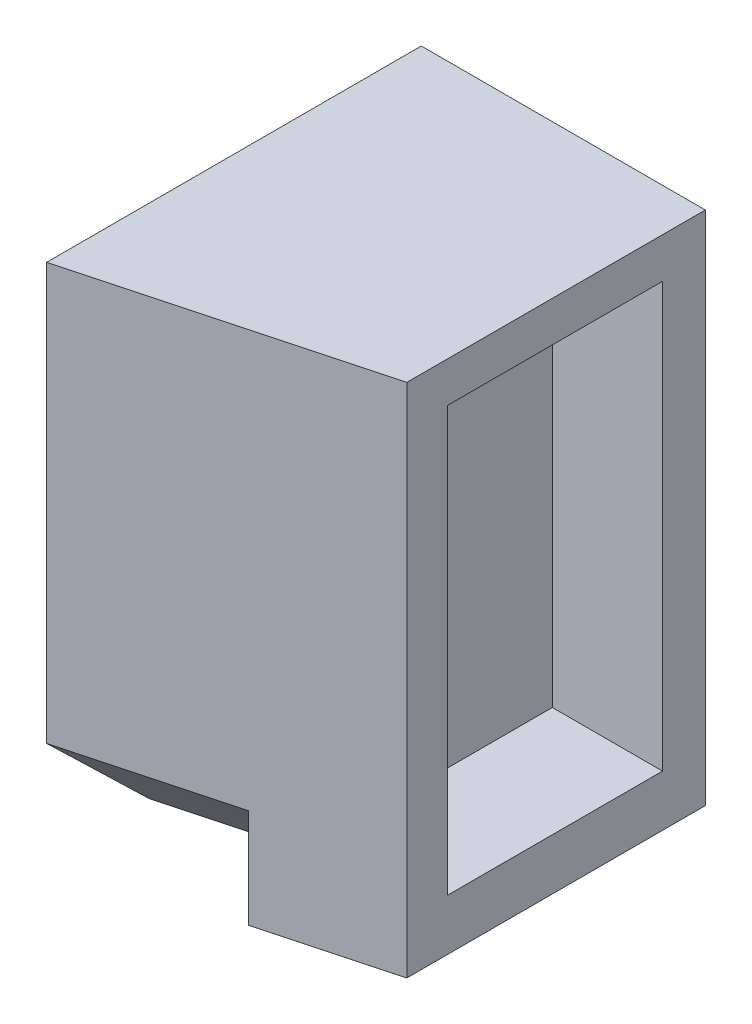
SolidWorks part; units mm, degrees
ref_plane "Front Plane" through (0, 0, 0) normal (0, 0, 1) x (1, 0, 0)
ref_plane "Top Plane" through (0, 0, 0) normal (0, 1, 0) x (1, 0, 0)
ref_plane "Right Plane" through (0, 0, 0) normal (1, 0, 0) x (0, 0, -1)
sketch3d "3DSketch1"
  line L2 (0, 594.6103, 215.9) -> (0, 0, 215.9) construction
  line L3 (327.3856, 0, 431.8) -> (327.3856, 0, 0) construction
  line L6 (0, 0, 0) -> (0, 594.6103, 0) construction
  line L7 (327.3856, 594.6103, 431.8) -> (327.3856, 594.6103, 0) construction
  line L8 (327.3856, 594.6103, 0) -> (327.3856, 0, 0) construction
  line L9 (0, 0, 431.8) -> (0, 594.6103, 431.8) construction
  line L10 (327.3856, 594.6103, 431.8) -> (0, 594.6103, 431.8) construction
  line L11 (327.3856, 0, 431.8) -> (327.3856, 594.6103, 431.8) construction
  line L12 (0, 594.6103, 431.8) -> (0, 594.6103, 0) construction
  line L13 (327.3856, 0, 431.8) -> (0, 0, 431.8) construction
  line L14 (327.3856, 594.6103, 0) -> (0, 594.6103, 0) construction
  line L15 (0, 0, 431.8) -> (0, 0, 0) construction
  line L16 (327.3856, 0, 0) -> (0, 0, 0) construction
  line L17 (0, 209.55, 215.9) -> (173.99, 209.55, 215.9) construction
  line L18 (0, 412.75, 291.084) -> (0, 563.88, 291.084) construction
  line L19 (0, 412.75, 291.084) -> (0, 412.75, 140.716) construction
  line L20 (0, 412.75, 140.716) -> (0, 563.88, 140.716) construction
  line L21 (0, 563.88, 291.084) -> (0, 563.88, 140.716) construction
  line L22 (0, 412.75, 291.084) -> (0, 563.88, 140.716) construction
  line L23 (0, 412.75, 140.716) -> (0, 563.88, 291.084) construction
  circle A0 centre (0, 209.55, 215.9) radius 196.85 construction
  point P11 (196.85, 209.55, 215.9)
  point P14 (0, 406.4, 215.9)
  point P15 (0, 12.7, 215.9)
  point P16 (0, 412.75, 215.9)
  point P17 (0, 488.315, 215.9)
  point P22 (0, 0, 0)
  point P24 (0, 0, 0)
  point P25 (0, 0, 0)
  dimension "D1" = 327.3856
  dimension "D4" = 393.7
  dimension "D2" = 431.8
  dimension "D3" = 594.6103
  dimension "D5" = 12.7
  dimension "D6" = 150.368
  dimension "D7" = 151.13
  dimension "D8" = 6.35
  dimension "D9" = 173.99
sketch "Sketch1" plane through (0, 0, 0) normal (1, 0, 0) x (0, 0, -1)
  line L0 (-414.2602, 721.6103) -> (-423.0301, 594.6103)
  line L4 (-414.2602, 721.6103) -> (-215.9, 721.6103)
  line L5 (-215.9, 721.6103) -> (-215.9, 594.6103) construction
  line L6 (-431.8, 594.6103) -> (0, 594.6103) construction
  line L8 (-423.0301, 594.6103) -> (-431.8, 467.6103)
  line L9 (-431.8, 0) -> (-431.8, 594.6103) construction
  point P0 (-299.3658, 631.7037)
  dimension "D1" = 127
  dimension "D2" = 198.3602
sketch "Sketch2" plane through (0, 0, 0) normal (0, 1, 0) x (1, 0, 0)
  line L0 (0, -431.8) -> (327.3856, -344.0773)
  line L1 (327.3856, -431.8) -> (327.3856, 0) construction
  line L3 (0, -431.8) -> (0, 0) construction
  line L5 (327.3856, -344.0773) -> (327.3856, 0)
  line L6 (327.3856, 0) -> (0, 0)
  line L7 (0, 0) -> (0, -431.8)
  dimension "D1" = 75
extrude "Boss-Extrude1" add sketch "Sketch2" along normal up to vertex (594.6103 mm away)
sketch "Sketch3" plane through (327.3856, 0, 0) normal (1, 0, 0) x (0, 0, -1)
  line L1 (-49.3464, 59.1545) -> (-296.9964, 59.1545)
  line L2 (-49.3464, 59.1545) -> (-49.3464, 548.1045)
  line L3 (-49.3464, 548.1045) -> (-296.9964, 548.1045)
  line L4 (-296.9964, 59.1545) -> (-296.9964, 548.1045)
  line L5 (-49.3464, 59.1545) -> (-296.9964, 548.1045) construction
  line L6 (-49.3464, 548.1045) -> (-296.9964, 59.1545) construction
  point P0 (-173.1714, 303.6295)
  point P5 (-173.1714, 303.6295)
  dimension "D1" = 247.65
  dimension "D2" = 488.95
extrude "Cut-Extrude1" cut sketch "Sketch3" against normal blind 127
sketch "Sketch4" plane through (0, 0, 0) normal (1, 0, 0) x (0, -1, 0)
  line L1 (-309.55, -340.9) -> (-109.55, -340.9)
  line L2 (-309.55, -340.9) -> (-309.55, -90.9)
  line L3 (-309.55, -90.9) -> (-109.55, -90.9)
  line L4 (-109.55, -340.9) -> (-109.55, -90.9)
  line L5 (-309.55, -340.9) -> (-109.55, -90.9) construction
  line L6 (-309.55, -90.9) -> (-109.55, -340.9) construction
  point P0 (-209.55, -215.9)
  point P5 (0, 0)
  point P6 (-141.6696, -165.947)
  point P7 (-222.25, -215.9)
  dimension "D1" = 200
  dimension "D2" = 250
extrude "Cut-Extrude2" cut sketch "Sketch4" along normal blind 100
sketch "Sketch5" plane through (0, 0, 0) normal (-1, 0, 0) x (0, 0, 1)
  line L1 (265.9, 438.315) -> (165.9, 438.315)
  line L2 (265.9, 438.315) -> (265.9, 538.315)
  line L3 (265.9, 538.315) -> (165.9, 538.315)
  line L4 (165.9, 438.315) -> (165.9, 538.315)
  line L5 (265.9, 438.315) -> (165.9, 538.315) construction
  line L6 (265.9, 538.315) -> (165.9, 438.315) construction
  point P0 (215.9, 488.315)
  dimension "D1" = 100
  dimension "D2" = 100
extrude "Cut-Extrude3" cut sketch "Sketch5" against normal blind 100
sketch "Sketch6" plane through (0, 0, 0) normal (-1, 0, 0) x (0, 0, 1)
  line L0 (0, 114.3) -> (114.3, 0)
  line L1 (0, 0) -> (0, 594.6103) construction
  line L2 (431.8, 0) -> (0, 0) construction
  line L3 (114.3, 0) -> (0, 0)
  line L4 (0, 0) -> (0, 114.3)
  dimension "D1" = 114.3
  dimension "D2" = 114.3
extrude "Cut-Extrude4" cut sketch "Sketch6" against normal blind 172
ref_plane "Plane1" through (-107.95, 0, 28.9251) normal (0.9659, 0, -0.2588) x (0, 1, 0)
sketch "Sketch7" plane through (-107.95, 0, 28.9251) normal (0.9659, 0, -0.2588) x (0, 1, 0)
  line L0 (0, 417.0868) -> (114.3, 417.0868)
  line L1 (0, 417.0868) -> (594.6103, 417.0868) construction
  line L2 (114.3, 417.0868) -> (0, 302.7868)
  line L3 (0, 302.7868) -> (0, 417.0868)
  dimension "D1" = 114.3
  dimension "D2" = 114.3
extrude "Cut-Extrude5" cut sketch "Sketch7" along normal blind 190
equation "\"depth\"= \"vol\" / \"width\" / \"height\""
equation "\"D1@3DSketch1\"=\"depth\""
equation "\"width\"= 15.5 + 2 * \"gap\""
equation "\"D2@3DSketch1\"=\"width\""
equation "\"height\"= \"width\" * ( 1 + 5 ^ ( 1 / 2 ) ) / 2.35"
equation "\"D3@3DSketch1\"=\"height\""
equation "\"vol\" = 61 * ( 50 + 5.2 + 0.5 + 0.5 + 3 + 2 ) + ( 19.25 * 9.75 * 5.5 ) + 364"
equation "\"gap\"= .75"
equation "\"WedgeVol\"= \"height\" * 0.5 * sin ( 15 ) * \"depth\" ^ 2'261"
equation "\"topHeight\"=5"
equation "\"topWidth\" = \"WedgeVol\" / \"depth\" / \"topHeight\""
equation "\"D2@Sketch1\"=\"topWidth\""
equation "\"D1@Sketch1\"=\"topHeight\""
